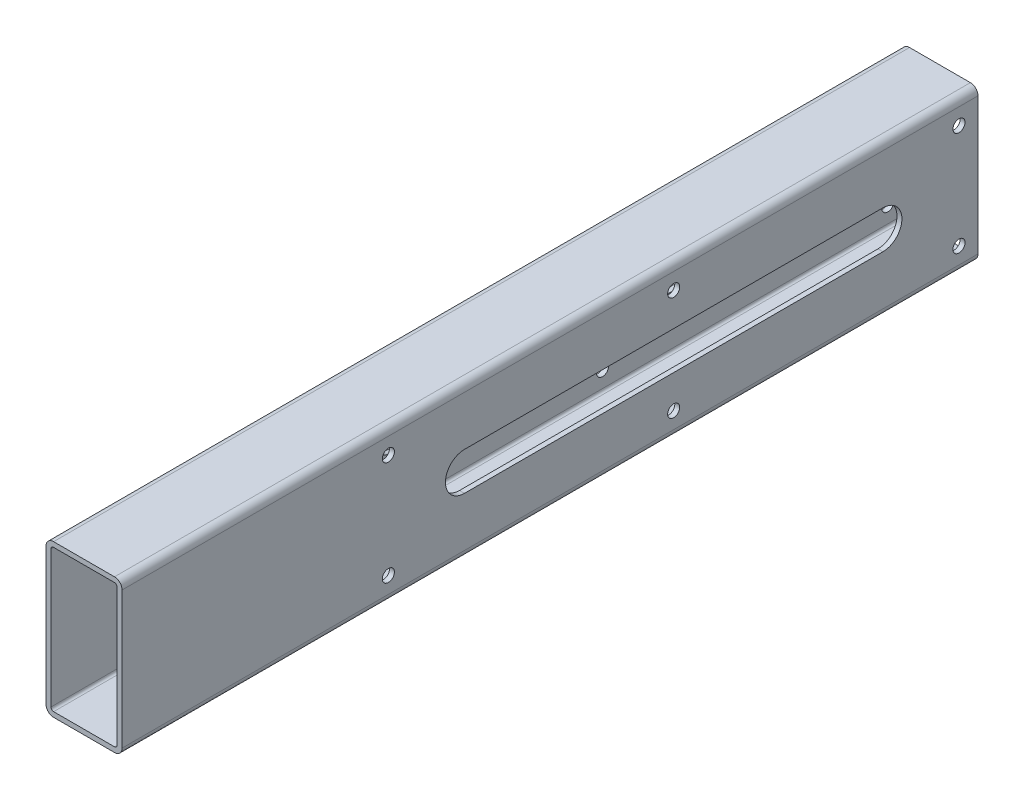
SolidWorks part; units mm, degrees
material "6061-T6 (SS)"
ref_plane "Front Plane" through (0, 0, 0) normal (0, 0, 1) x (1, 0, 0)
ref_plane "Top Plane" through (0, 0, 0) normal (0, 1, 0) x (1, 0, 0)
ref_plane "Right Plane" through (0, 0, 0) normal (1, 0, 0) x (0, 0, -1)
sketch "Sketch1" plane through (0, 0, 0) normal (0, 0, 1) x (1, 0, 0)
  line L1 (10.16, -25.4) -> (-10.16, -25.4)
  line L2 (12.7, -22.86) -> (12.7, 22.86)
  line L3 (10.16, 25.4) -> (-10.16, 25.4)
  line L4 (-12.7, -22.86) -> (-12.7, 22.86)
  line L5 (12.7, -25.4) -> (-12.7, 25.4) construction
  line L6 (12.7, 25.4) -> (-12.7, -25.4) construction
  arc A0 (-10.16, -25.4) -> (-12.7, -22.86) centre (-10.16, -22.86) cw
  arc A1 (10.16, -25.4) -> (12.7, -22.86) centre (10.16, -22.86) ccw
  arc A2 (12.7, 22.86) -> (10.16, 25.4) centre (10.16, 22.86) ccw
  arc A3 (-10.16, 25.4) -> (-12.7, 22.86) centre (-10.16, 22.86) ccw
  point P0 (0, 0)
  dimension "D3" = 2.54
  dimension "D1" = 25.4
  dimension "D2" = 50.8
extrude "Extrude-Thin1" add sketch "Sketch1" along normal blind 285.75 thin
sketch "Sketch2" plane through (-12.7, 0, 0) normal (-1, 0, 0) x (0, 0, 1)
  line L0 (31.75, 0) -> (171.45, 0) construction
  line L1 (31.75, 6.35) -> (171.45, 6.35)
  line L2 (31.75, -6.35) -> (171.45, -6.35)
  line L3 (0, 22.86) -> (0, -22.86) construction
  arc A0 (31.75, 6.35) -> (31.75, -6.35) centre (31.75, 0) ccw
  arc A1 (171.45, -6.35) -> (171.45, 6.35) centre (171.45, 0) ccw
  point P3 (101.6, 0)
  dimension "D1" = 12.7
  dimension "D2" = 139.7
  dimension "D3" = 31.75
extrude "Cut-Extrude1" cut sketch "Sketch2" against normal through all
sketch "Sketch3" [suppressed] plane through (-12.7, 0, 0) normal (-1, 0, 0) x (0, 0, 1)
  line L0 (571.5, 0) -> (444.5, 0) construction
  line L1 (571.5, -6.35) -> (444.5, -6.35)
  line L2 (571.5, 6.35) -> (444.5, 6.35)
  line L3 (736.6, 22.86) -> (736.6, -22.86) construction
  arc A0 (571.5, -6.35) -> (571.5, 6.35) centre (571.5, 0) ccw
  arc A1 (444.5, 6.35) -> (444.5, -6.35) centre (444.5, 0) ccw
  point P3 (508, 0)
  dimension "D1" = 12.7
  dimension "D2" = 165.1
  dimension "D3" = 127
extrude "Cut-Extrude2" [suppressed] cut sketch "Sketch3" against normal through all
sketch "Sketch4" plane through (12.7, 0, 0) normal (1, 0, 0) x (0, 0, -1)
  circle A0 centre (-196.85, 17.399) radius 2.0193 construction
  circle A1 centre (-196.85, -17.399) radius 2.0193 construction
  circle A2 centre (-101.6, 17.399) radius 2.0193 construction
  circle A3 centre (-101.6, -17.399) radius 2.0193 construction
  circle A4 centre (-6.35, 17.399) radius 2.0193 construction
  circle A5 centre (-6.35, -17.399) radius 2.0193 construction
  circle A6 centre (-196.85, 17.399) radius 2.0193
  circle A7 centre (-196.85, -17.399) radius 2.0193
  circle A8 centre (-101.6, 17.399) radius 2.0193
  circle A9 centre (-101.6, -17.399) radius 2.0193
  circle A10 centre (-6.35, 17.399) radius 2.0193
  circle A11 centre (-6.35, -17.399) radius 2.0193
extrude "Cut-Extrude3" cut sketch "Sketch4" against normal through all
